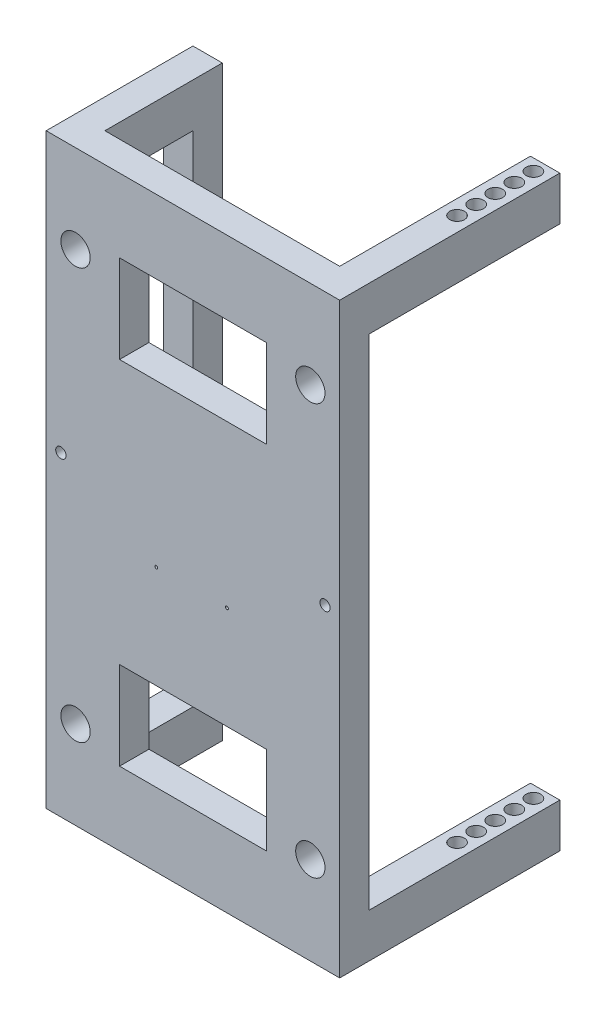
SolidWorks part; units mm, degrees
material "POM Acetal Copolymer"
ref_plane "Front Plane" through (0, 0, 0) normal (0, 0, 1) x (1, 0, 0)
ref_plane "Top Plane" through (0, 0, 0) normal (0, 1, 0) x (1, 0, 0)
ref_plane "Right Plane" through (0, 0, 0) normal (1, 0, 0) x (0, 0, -1)
sketch "Sketch2" plane through (0, 0, 0) normal (0, 1, 0) x (1, 0, 0)
  line L0 (0, 0) -> (0, 100)
  line L1 (0, 100) -> (20, 100)
  line L2 (20, 100) -> (20, 20)
  line L3 (20, 20) -> (180, 20)
  line L4 (180, 20) -> (180, 150)
  line L5 (180, 150) -> (200, 150)
  line L6 (200, 150) -> (200, 0)
  line L7 (200, 0) -> (0, 0)
  dimension "D1" = 200
  dimension "D2" = 150
  dimension "D3" = 20
  dimension "D4" = 100
  dimension "D5" = 20
  dimension "D6" = 80
extrude "Boss-Extrude1" add sketch "Sketch2" against normal blind 400 contours L7 L0 L1 L2 L3 L4 L5 L6
sketch "Sketch3" plane through (0, 0, 0) normal (0, 0, 1) x (1, 0, 0)
  line L1 (50, -50) -> (150, -50)
  line L2 (50, -50) -> (50, -350)
  line L3 (50, -350) -> (150, -350)
  line L4 (150, -50) -> (150, -350)
  line L5 (200, -400) -> (0, -400) construction
  line L6 (200, -400) -> (200, 0) construction
  dimension "D1" = 100
  dimension "D2" = 300
  dimension "D3" = 50
  dimension "D4" = 50
extrude "Cut-Extrude1" cut sketch "Sketch3" against normal blind 400
sketch "Sketch4" plane through (0, 0, 0) normal (-1, 0, 0) x (0, 0, 1)
  line L0 (0, 0) -> (-100, 0) construction
  line L1 (-20, -30) -> (-80, -30)
  line L2 (-20, -30) -> (-20, -370)
  line L3 (-20, -370) -> (-80, -370)
  line L4 (-80, -30) -> (-80, -370)
  line L6 (0, -400) -> (0, 0) construction
  dimension "D1" = 340
  dimension "D2" = 30
  dimension "D3" = 20
  dimension "D4" = 60
extrude "Cut-Extrude2" cut sketch "Sketch4" against normal blind 400
sketch "Sketch5" plane through (200, 0, 0) normal (1, 0, 0) x (0, 0, -1)
  line L5 (150, -400) -> (150, 0) construction
  line L6 (80, -30) -> (150, -30)
  line L7 (80, -30) -> (80, -370)
  line L8 (80, -370) -> (150, -370)
  line L9 (150, -30) -> (150, -370)
  dimension "D1" = 340
extrude "Cut-Extrude4" cut sketch "Sketch5" against normal blind 118
sketch "Sketch6" plane through (0, 0, 0) normal (0, 1, 0) x (1, 0, 0)
  line L0 (180, 150) -> (200, 150) construction
  line L1 (180, 20) -> (180, 150) construction
  circle A0 centre (190, 142) radius 5
  circle A5 centre (190, 129) radius 5
  circle A6 centre (190, 116) radius 5
  circle A7 centre (190, 103) radius 5
  circle A8 centre (190, 90) radius 5
  dimension "D1" = 10
  dimension "D2" = 8
  dimension "D4" = 10
  dimension "D5" = 13
  dimension "D3" = 5
extrude "Cut-Extrude5" cut sketch "Sketch6" against normal blind 543
sketch "Sketch7" plane through (0, 0, 0) normal (-1, 0, 0) x (0, 0, 1)
  line L0 (-100, -400) -> (-100, 0) construction
  line L1 (0, 0) -> (-100, 0) construction
  line L2 (0, -400) -> (-100, -400) construction
  circle A0 centre (-90, -80) radius 5
  circle A1 centre (-90, -320) radius 5
  dimension "D1" = 10
  dimension "D2" = 10
  dimension "D3" = 80
  dimension "D4" = 10
  dimension "D5" = 10
  dimension "D6" = 80
extrude "Cut-Extrude6" cut sketch "Sketch7" against normal blind 193
cosmetic thread "Cosmetic Thread3" parameters "D2"=11
cosmetic thread "Cosmetic Thread4" parameters "D2"=11
sketch "Sketch8" plane through (0, 0, 0) normal (0, 0, 1) x (1, 0, 0)
  line L0 (200, 0) -> (0, 0) construction
  line L1 (200, -400) -> (200, 0) construction
  line L2 (0, -400) -> (0, 0) construction
  line L3 (200, -400) -> (0, -400) construction
  circle A0 centre (180, -60) radius 10
  circle A1 centre (20, -60) radius 10
  circle A2 centre (180, -340) radius 10
  circle A3 centre (20, -340) radius 10
  dimension "D1" = 20
  dimension "D2" = 20
  dimension "D3" = 20
  dimension "D4" = 20
  dimension "D5" = 60
  dimension "D6" = 20
  dimension "D7" = 60
  dimension "D8" = 20
  dimension "D9" = 20
  dimension "D10" = 60
  dimension "D11" = 60
  dimension "D12" = 20
extrude "Cut-Extrude7" cut sketch "Sketch8" against normal up to surface (20 mm away) up to face at (100, -200, -20)
cosmetic thread "Cosmetic Thread5" parameters "D2"=21
cosmetic thread "Cosmetic Thread6" parameters "D2"=21
cosmetic thread "Cosmetic Thread7" parameters "D2"=21
cosmetic thread "Cosmetic Thread8" parameters "D2"=21
sketch "Sketch9" plane through (0, 0, 0) normal (0, 0, 1) x (1, 0, 0)
  line L0 (50, -50) -> (50, -350) construction
  line L1 (50, -110) -> (150, -110)
  line L2 (50, -110) -> (50, -290)
  line L3 (50, -290) -> (150, -290)
  line L4 (150, -110) -> (150, -290)
  line L5 (150, -350) -> (150, -50) construction
  line L6 (150, -50) -> (50, -50) construction
  line L7 (50, -350) -> (150, -350) construction
  dimension "D1" = 60
  dimension "D2" = 60
extrude "Boss-Extrude2" add sketch "Sketch9" against normal blind 20
sketch "Sketch11" plane through (0, 0, 0) normal (0, 0, 1) x (1, 0, 0)
  line L0 (200, -400) -> (0, -400) construction
  line L1 (0, -400) -> (0, 0) construction
  line L2 (200, -400) -> (200, 0) construction
  circle A0 centre (75, -220) radius 1
  circle A1 centre (123.17, -220) radius 1
  dimension "D1" = 180
  dimension "D2" = 75
  dimension "D3" = 2
  dimension "D4" = 2
  dimension "D5" = 48.17
  dimension "D6" = 76.83
extrude "Cut-Extrude8" cut sketch "Sketch11" against normal mid plane 53
cosmetic thread "Cosmetic Thread9" parameters "D2"=3
cosmetic thread "Cosmetic Thread10" parameters "D2"=3
sketch "Sketch12" plane through (0, 0, 0) normal (0, 0, 1) x (1, 0, 0)
  line L0 (200, -400) -> (0, -400) construction
  line L2 (200, -400) -> (200, 0) construction
  circle A1 centre (190, -185) radius 3.5
  dimension "D4" = 10
  dimension "D5" = 7
  dimension "D6" = 215
extrude "Cut-Extrude9" cut sketch "Sketch12" against normal blind 35
cosmetic thread "Cosmetic Thread12" parameters "D2"=8
ref_plane "Plane1" through (100, 0, 0) normal (1, 0, 0) x (0, 0, -1)
mirror "Mirror1" about plane through (100, 0, 0) normal (1, 0, 0) of "Cut-Extrude9"
cosmetic thread "Cosmetic Thread13" parameters "D2"=8
